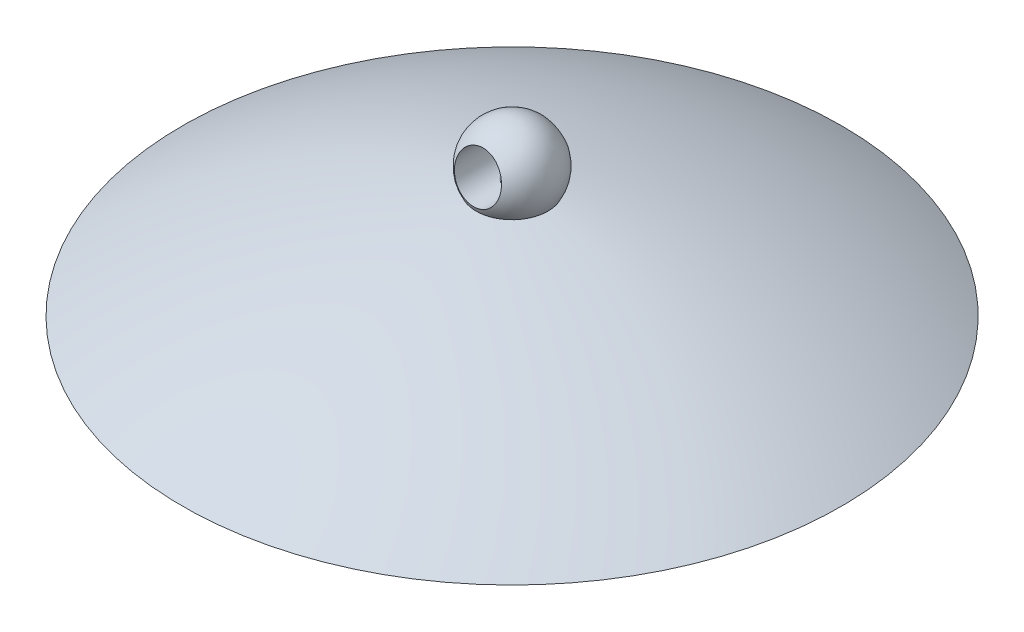
SolidWorks part; units mm, degrees
ref_plane "Plano frontal" through (0, 0, 0) normal (0, 0, 1) x (1, 0, 0)
ref_plane "Plano superior" through (0, 0, 0) normal (0, 1, 0) x (1, 0, 0)
ref_plane "Plano direito" through (0, 0, 0) normal (1, 0, 0) x (0, 0, -1)
sketch "Esboço1" plane through (0, 0, 0) normal (0, 0, 1) x (1, 0, 0)
  line L0 (0, 0) -> (-53.5, 0)
  line L1 (0, 0) -> (0, 18.3232)
  line L3 (0, 23.8882) -> (0, 25.6987)
  line L4 (0, 25.6987) -> (0, 27.8882)
  arc A1 (0, 23.8882) -> (0, 18.3232) centre (0, 21.1057) ccw
  arc A2 (0, 27.8882) -> (-5.8344, 17.647) centre (0, 21.1057) ccw
  arc A3 (-53.5, 0) -> (-5.8344, 17.647) centre (15.7031, -113.7242) cw
  arc A4 (0, 27.8882) -> (0, 14.3232) centre (0, 21.1057) ccw construction
  dimension "D1" = 53.5
  dimension "D2" = 4
revolve "Revolução1" add sketch "Esboço1" angle 360 about L1
sketch "Esboço2" plane through (0, 0, 0) normal (0, 0, 1) x (1, 0, 0)
  circle A0 centre (0, 22.2446) radius 3.7431
extrude "Corte-extrusão1" cut sketch "Esboço2" against normal through all and the other way through all
